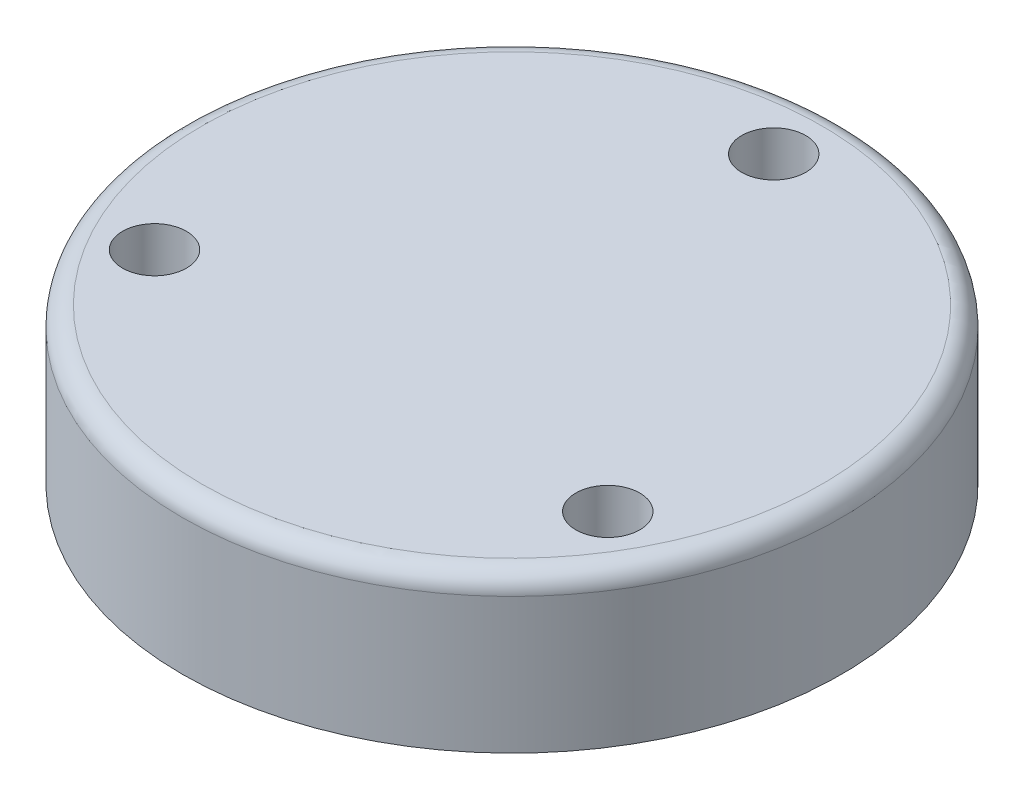
SolidWorks part; units mm, degrees
ref_plane "Спереди" through (0, 0, 0) normal (0, 0, 1) x (1, 0, 0)
ref_plane "Сверху" through (0, 0, 0) normal (0, 1, 0) x (1, 0, 0)
ref_plane "Справа" through (0, 0, 0) normal (1, 0, 0) x (0, 0, -1)
sketch "Эскиз1" plane through (0, 0, 0) normal (0, 1, 0) x (1, 0, 0)
  circle A0 centre (0, 0) radius 17
  dimension "D1" = 34
extrude "Бобышка-Вытянуть1" add sketch "Эскиз1" along normal blind 8
sketch "Эскиз3" plane through (0, 0, 0) normal (0, -1, 0) x (-1, 0, 0)
  line L0 (0, 60.1908) -> (0, -20) construction
  line L1 (0, -20) -> (69.2842, -20) construction
  line L5 (-9, -70) -> (9, -70)
  line L6 (-9, -70) -> (-9, 30)
  line L7 (-9, 30) -> (9, 30)
  line L8 (9, -70) -> (9, 30)
  line L9 (0, 30) -> (0, -70) construction
  line L10 (-9, -20) -> (9, -20) construction
  dimension "D2" = 100
  dimension "D1" = 18
  dimension "D3" = 20
extrude "Бобышка-Вытянуть2" [suppressed] add sketch "Эскиз3" along normal blind 12
sketch "Эскиз2" plane through (0, 8, 0) normal (0, 1, 0) x (1, 0, 0)
  line L0 (0, 18.4133) -> (0, 0) construction
  line L1 (0, 0) -> (22.5214, 0) construction
  circle A0 centre (0, 0) radius 13.5 construction
  circle A1 centre (0, 13.5) radius 1.65
  circle A2 centre (11.6913, -6.75) radius 1.65
  circle A3 centre (-11.6913, -6.75) radius 1.65
  dimension "D1" = 27
  dimension "D2" = 3.3
  dimension "D3" = 3
extrude "Вырез-Вытянуть1" cut sketch "Эскиз2" against normal blind 20
fillet "Скругление1" radius 1 1 edges at (0, 8, 17)
sketch "Эскиз4" [suppressed] plane through (0, 0, -30) normal (0, 0, -1) x (-1, 0, 0)
  line L0 (0, -1.5497) -> (0, -9) construction
  line L1 (0, -9) -> (15.3096, -9) construction
  line L2 (9, -12) -> (-9, -12) construction
  circle A0 centre (0, -9) radius 8
  dimension "D1" = 3
extrude "Вырез-Вытянуть2" [suppressed] cut sketch "Эскиз4" against normal through all
